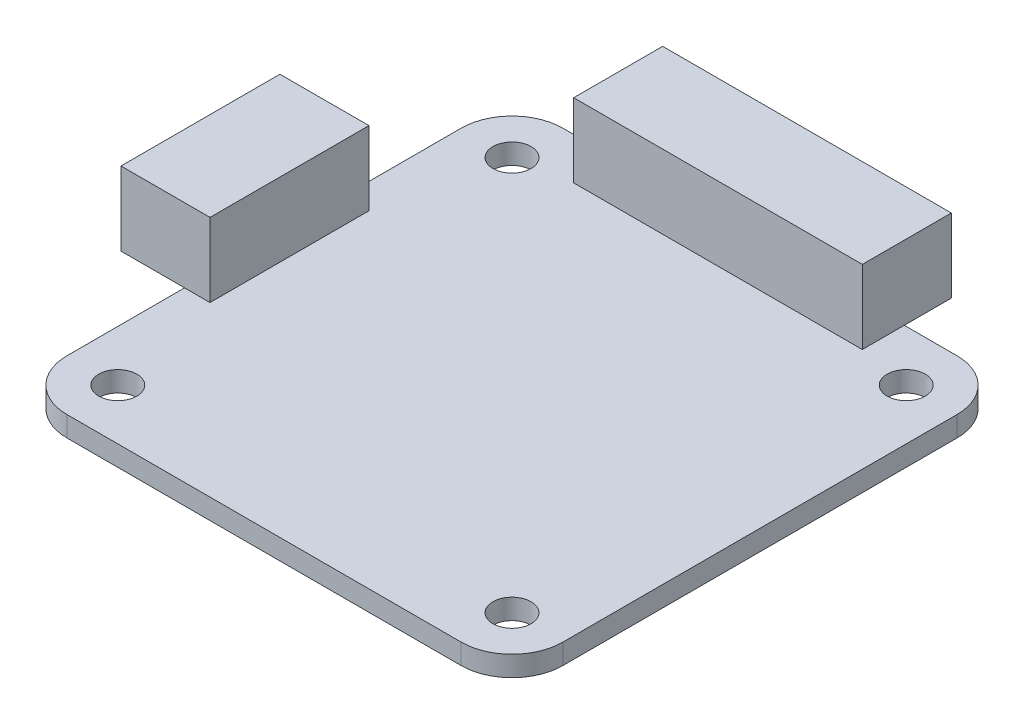
SolidWorks part; units mm, degrees
ref_plane "前视基准面" through (0, 0, 0) normal (0, 0, 1) x (1, 0, 0)
ref_plane "上视基准面" through (0, 0, 0) normal (0, 1, 0) x (1, 0, 0)
ref_plane "右视基准面" through (0, 0, 0) normal (1, 0, 0) x (0, 0, -1)
other "Configuration Table"
sketch "草图1" plane through (0, 0, 0) normal (0, 1, 0) x (1, 0, 0)
  line L1 (-15.5, -19.5) -> (15.5, -19.5)
  line L2 (-19.5, -15.5) -> (-19.5, 15.5)
  line L3 (-15.5, 19.5) -> (15.5, 19.5)
  line L4 (19.5, -15.5) -> (19.5, 15.5)
  line L5 (-19.5, -19.5) -> (19.5, 19.5) construction
  line L6 (-19.5, 19.5) -> (19.5, -19.5) construction
  line L7 (-15.5, -15.5) -> (15.5, -15.5) construction
  line L8 (-15.5, -15.5) -> (-15.5, 15.5) construction
  line L9 (-15.5, 15.5) -> (15.5, 15.5) construction
  line L10 (15.5, -15.5) -> (15.5, 15.5) construction
  line L11 (-15.5, -15.5) -> (15.5, 15.5) construction
  line L12 (-15.5, 15.5) -> (15.5, -15.5) construction
  circle A0 centre (-15.5, -15.5) radius 1.5
  circle A1 centre (15.5, -15.5) radius 1.5
  circle A2 centre (-15.5, 15.5) radius 1.5
  circle A3 centre (15.5, 15.5) radius 1.5
  arc A4 (-15.5, 19.5) -> (-19.5, 15.5) centre (-15.5, 15.5) ccw
  arc A5 (19.5, 15.5) -> (15.5, 19.5) centre (15.5, 15.5) ccw
  arc A6 (-19.5, -15.5) -> (-15.5, -19.5) centre (-15.5, -15.5) ccw
  arc A7 (15.5, -19.5) -> (19.5, -15.5) centre (15.5, -15.5) ccw
  point P0 (0, 0)
  point P6 (0, 0)
  dimension "D5" = 3
  dimension "D6" = 3
  dimension "D7" = 3
  dimension "D8" = 3
  dimension "D12" = 8
  dimension "D13" = 31
  dimension "D2" = 19.5
  dimension "D3" = 31
  dimension "D4" = 31
  dimension "D9" = 39
  dimension "D10" = 39
  dimension "D11" = 31
  dimension "D14" = 39
  dimension "D15" = 19.5
extrude "凸台-拉伸1" add sketch "草图1" along normal blind 1.6
sketch "草图2" plane through (0, 0, 0) normal (0, 1, 0) x (1, 0, 0)
  line L0 (0, -1000) -> (0, 49000) construction
  line L1 (-1000, 0) -> (49000, 0) construction
  line L2 (15.5, 19.5) -> (-15.5, 19.5) construction
  line L3 (-11.35, 23.2) -> (11.35, 23.2)
  line L4 (-11.35, 23.2) -> (-11.35, 16.2)
  line L5 (-11.35, 16.2) -> (11.35, 16.2)
  line L6 (11.35, 23.2) -> (11.35, 16.2)
  line L7 (-19.5, 15.5) -> (-19.5, -15.5) construction
  line L8 (-24.5, 6.25) -> (-17.5, 6.25)
  line L9 (-24.5, 6.25) -> (-24.5, -6.25)
  line L10 (-24.5, -6.25) -> (-17.5, -6.25)
  line L11 (-17.5, 6.25) -> (-17.5, -6.25)
  point P9 (0, 16.2)
  point P18 (-17.5, 0)
  dimension "D1" = 22.7
  dimension "D2" = 7
  dimension "D3" = 3.3
  dimension "D4" = 12.5
  dimension "D5" = 7
  dimension "D6" = 2
extrude "凸台-拉伸2" add sketch "草图2" along normal blind 5.8 from surface at 1.6 starting at face at (-15.5, 1.6, -14)
